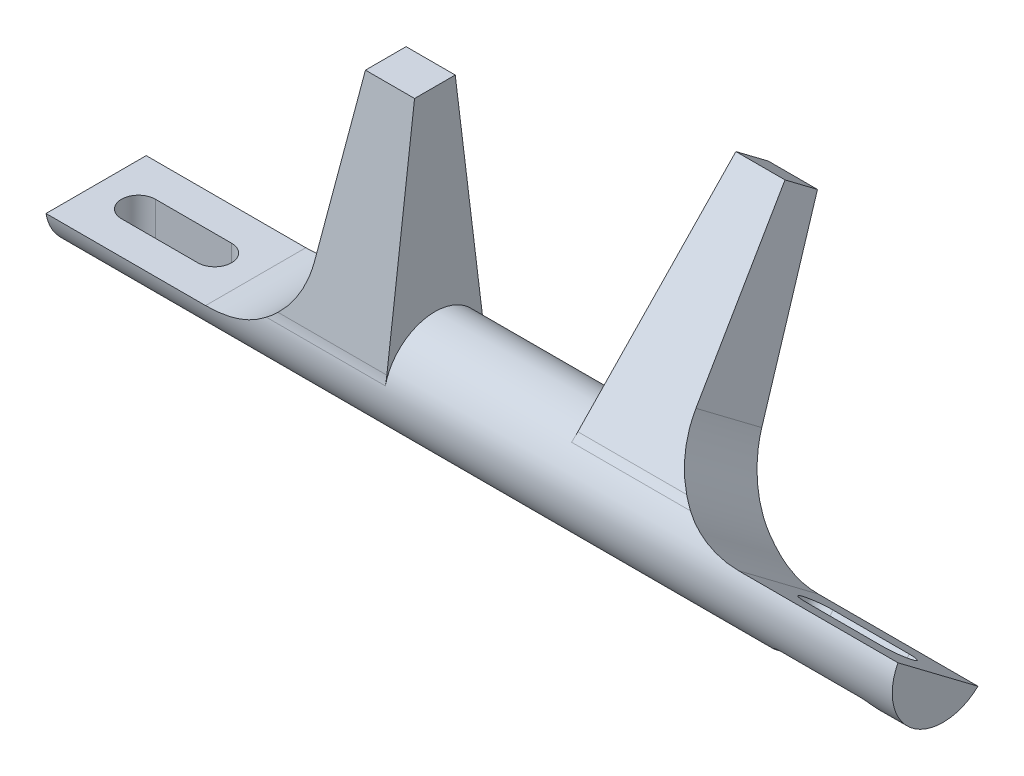
SolidWorks part; units mm, degrees
ref_plane "前视基准面" through (0, 0, 0) normal (0, 0, 1) x (1, 0, 0)
ref_plane "上视基准面" through (0, 0, 0) normal (0, 1, 0) x (1, 0, 0)
ref_plane "右视基准面" through (0, 0, 0) normal (1, 0, 0) x (0, 0, -1)
other "Configuration Table"
sketch "草图1" plane through (0, 0, 0) normal (1, 0, 0) x (0, 0, -1)
  circle A0 centre (0, 0) radius 30
  dimension "D1" = 60
extrude "凸台-拉伸1" add sketch "草图1" against normal blind 250
sketch "草图2" plane through (0, 0, 0) normal (1, 0, 0) x (0, 0, -1)
  line L0 (0, 207.0207) -> (0, 0) construction
  line L1 (-12, 145) -> (12, 145)
  line L2 (12, 145) -> (28.3653, 11.7153)
  line L3 (-12, 145) -> (-28.3653, 11.7153)
  arc A0 (28.3653, 11.7153) -> (29.2472, 6.6783) centre (77.9926, 17.8088) ccw
  circle A1 centre (0, 0) radius 30 construction
  circle A2 centre (0, 0) radius 30
  arc A3 (-28.3653, 11.7153) -> (-29.2472, 6.6783) centre (-77.9926, 17.8088) cw
  point P10 (4.7883, 145)
  point P11 (0, 207.0207)
  point P17 (0, 145)
  circle M1 centre (0, 0) radius 30
  dimension "D4" = 50
  dimension "D1" = 145
  dimension "D2" = 24
  dimension "D3" = 7
extrude "凸台-拉伸2" add sketch "草图2" against normal blind 200 from offset 50 contours L0 L1 L3 A3 A2 | L1 L0 A0 L2 M1 offset against normal yes
sketch "草图3" plane through (0, 0, 0) normal (0, 0, 1) x (1, 0, 0)
  line L0 (-79, 145) -> (-96.7066, 44.5811)
  line L1 (-250, 145) -> (-50, 145) construction
  line L2 (-155.795, -5) -> (-250, -5)
  line L3 (-250, 145) -> (-250, 11.7153) construction
  line L4 (0, 0) -> (-298.0362, 0) construction
  line L5 (-50, 145) -> (-50, 11.7153) construction
  arc A0 (-96.7066, 44.5811) -> (-155.795, -5) centre (-155.795, 55) cw
  dimension "D4" = 60
  dimension "D1" = 5
  dimension "D2" = 29
  dimension "D3" = 10
extrude "切除-拉伸2" cut sketch "草图3" against normal through all and the other way through all flip side to cut
sketch "草图4" plane through (0, -5, 0) normal (0, 1, 0) x (1, 0, 0)
  line L0 (0, 0) -> (-273.9507, 0) construction
  line L1 (-225, 0) -> (-180, 0) construction
  line L2 (-225, 10) -> (-180, 10)
  line L3 (-225, -10) -> (-180, -10)
  line L4 (-250, -29.5804) -> (-250, 29.5804) construction
  arc A0 (-225, 10) -> (-225, -10) centre (-225, 0) ccw
  arc A1 (-180, -10) -> (-180, 10) centre (-180, 0) ccw
  point P5 (-202.5, 0)
  dimension "D1" = 25
  dimension "D2" = 20
  dimension "D3" = 45
extrude "切除-拉伸3" cut sketch "草图4" against normal through all
mirror "镜向1" about plane through (0, 0, 0) normal (1, 0, 0) of bodies 110
move or copy body "实体-移动/复制1" bodies to move or copy 111 copy no rotation origin (0, 0, 0) rotation axis (-1, 0, 0) rotation angle 37
combine bodies "组合1" operation type add bodies to combine 110 112
